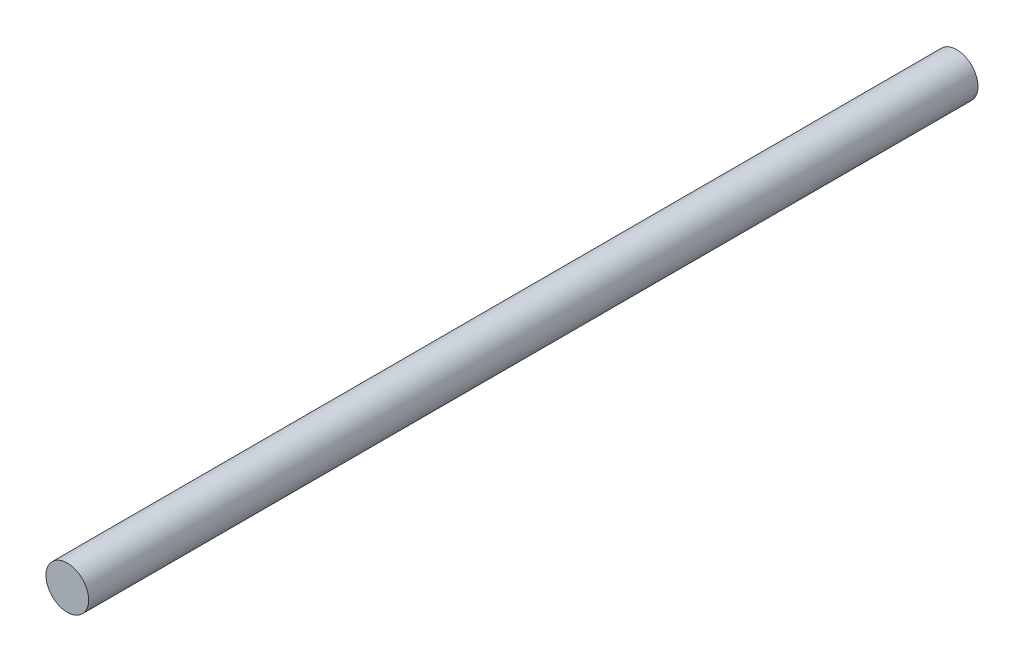
SolidWorks part; units mm, degrees
material "6063-O, Extruded Rod (SS)"
ref_plane "Front Plane" through (0, 0, 0) normal (0, 0, 1) x (1, 0, 0)
ref_plane "Top Plane" through (0, 0, 0) normal (0, 1, 0) x (1, 0, 0)
ref_plane "Right Plane" through (0, 0, 0) normal (1, 0, 0) x (0, 0, -1)
sketch "Sketch1" plane through (0, 0, 0) normal (0, 0, 1) x (1, 0, 0)
  circle A0 centre (0, 0) radius 3
  dimension "D1" = 6
extrude "Boss-Extrude1" add sketch "Sketch1" along normal blind 125
